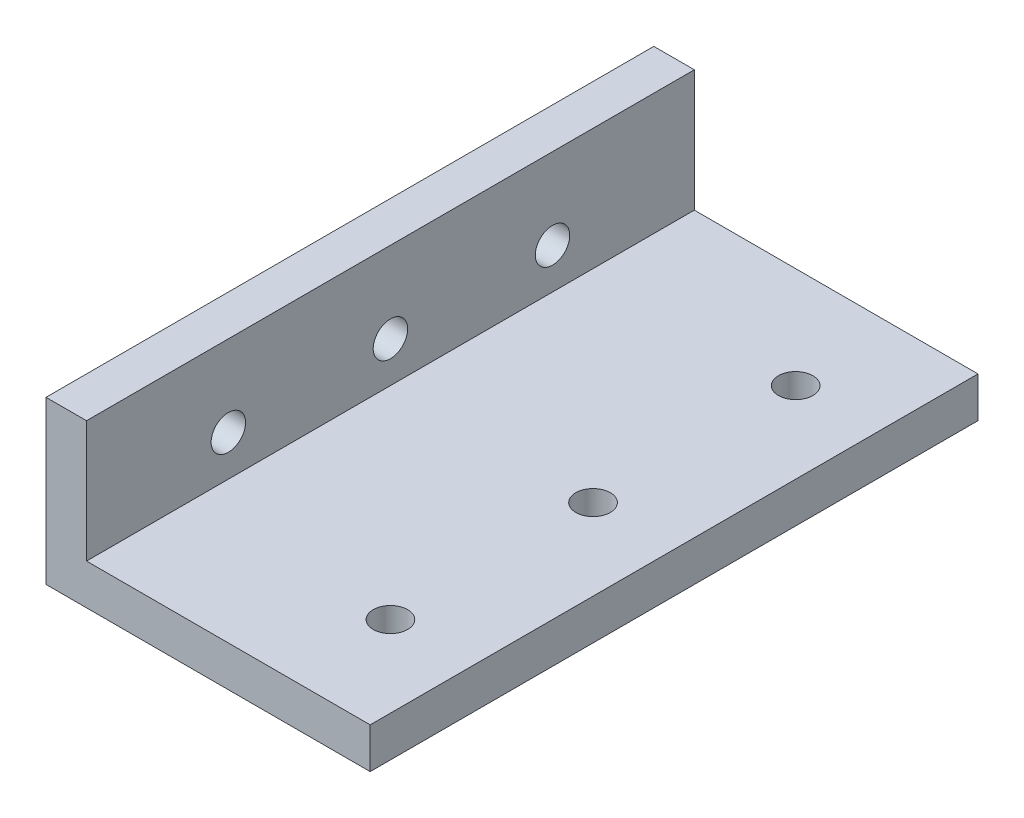
SolidWorks part; units mm, degrees
material "A6061"
ref_plane "前视基准面" through (0, 0, 0) normal (0, 0, 1) x (1, 0, 0)
ref_plane "上视基准面" through (0, 0, 0) normal (0, 1, 0) x (1, 0, 0)
ref_plane "右视基准面" through (0, 0, 0) normal (1, 0, 0) x (0, 0, -1)
sketch "草图1" plane through (0, 0, 0) normal (0, 0, 1) x (1, 0, 0)
  line L0 (0, 40) -> (0, 0)
  line L1 (0, 0) -> (80, 0)
  line L2 (80, 0) -> (80, 10)
  line L3 (80, 10) -> (10, 10)
  line L4 (10, 10) -> (10, 40)
  line L5 (10, 40) -> (0, 40)
  dimension "D1" = 10
  dimension "D2" = 10
  dimension "D3" = 40
  dimension "D4" = 80
extrude "凸台-拉伸1" add sketch "草图1" along normal blind 150
sketch "草图2" plane through (0, 10, 0) normal (0, 1, 0) x (1, 0, 0)
sketch "草图3" plane through (0, 10, 0) normal (0, 1, 0) x (1, 0, 0)
  line L0 (60, 4.4006) -> (60, -68.7068) construction
  line L1 (80, -150) -> (80, 0) construction
  line L2 (0, -75) -> (80, -75) construction
  line L3 (0, -150) -> (0, 0) construction
  circle A0 centre (60, -25) radius 3
  circle A1 centre (60, -75) radius 3
  circle A2 centre (60, -125) radius 3
  dimension "D2" = 6
  dimension "D3" = 100
  dimension "D1" = 20
sketch "草图4" plane through (10, 0, 0) normal (1, 0, 0) x (0, 0, -1)
  line L0 (-63.9435, 20) -> (8.2376, 20) construction
  line L1 (-75, 0) -> (-75, 43.2285) construction
  line L2 (-150, 0) -> (0, 0) construction
  line L3 (-150, 40) -> (0, 40) construction
  circle A0 centre (-35, 20) radius 3
  circle A1 centre (-75, 20) radius 3
  circle A2 centre (-115, 20) radius 3
  dimension "D1" = 6
  dimension "D3" = 80
  dimension "D2" = 20
hole_wizard "Ø8.5 (8.5) 直径孔1" positions "3D草图1" profile "草图5" hole size "Ø8.5" standard "GB" end condition through all
sketch3d "3D草图1"
  point P0 (10, 20, 115)
  point P6 (10, 20, 35)
  point P9 (60, 10, 125)
  point P15 (60, 10, 25)
  point P18 (10, 20, 75)
  point P21 (60, 10, 75)
sketch "草图5" plane through (10, 20, 115) normal (0, 1, 0) x (0, 0, -1)
  line L0 (0, 0) -> (0, 10)
  line L1 (0, 10) -> (4.25, 10)
  line L2 (4.25, 10) -> (4.25, 0)
  line L5 (4.25, 0) -> (0, 0)
  line L11 (0, -6.35) -> (0, 107.95) construction
  dimension "通孔孔直径" = 8.5
  dimension "通孔孔深度" = 10
